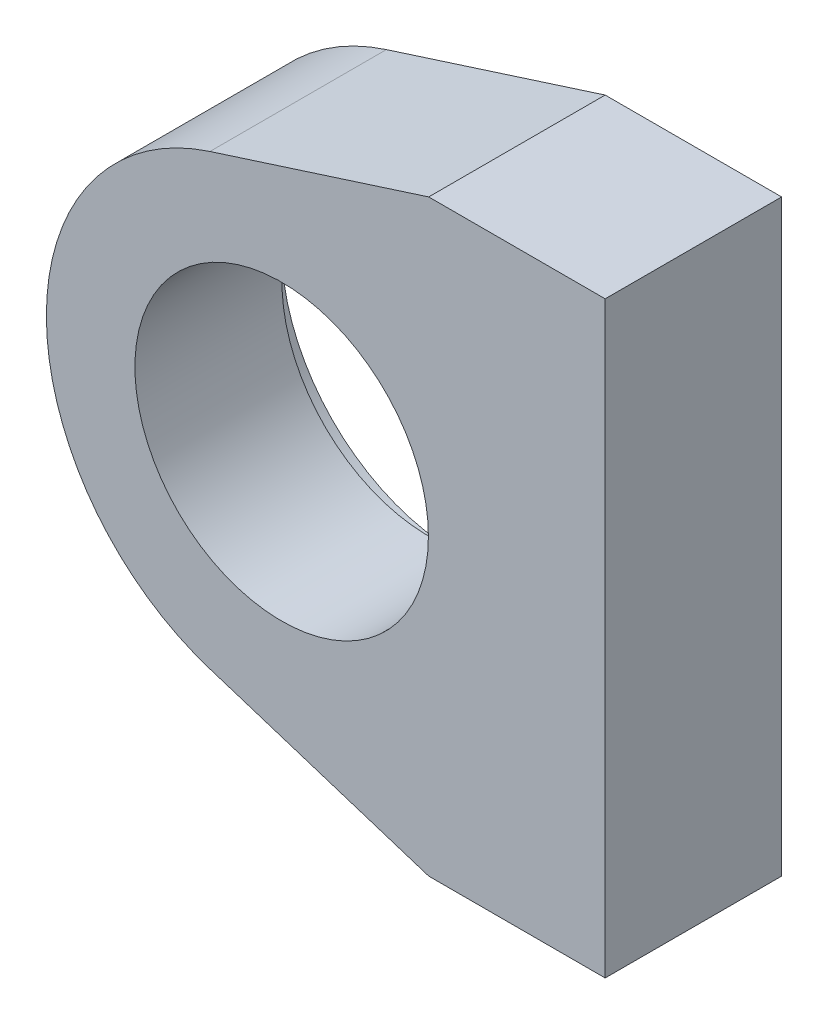
SolidWorks part; units mm, degrees
ref_plane "Front Plane" through (0, 0, 0) normal (0, 0, 1) x (1, 0, 0)
ref_plane "Top Plane" through (0, 0, 0) normal (0, 1, 0) x (1, 0, 0)
ref_plane "Right Plane" through (0, 0, 0) normal (1, 0, 0) x (0, 0, -1)
sketch "Sketch1" plane through (0, 0, 0) normal (0, 0, 1) x (1, 0, 0)
  line L0 (-2.4386, 7.6193) -> (5, 10)
  line L1 (5, -10) -> (11, -10)
  line L2 (-2.4386, -7.6193) -> (5, -10)
  line L3 (5, 10) -> (11, 10)
  line L4 (11, -10) -> (11, 10)
  circle A0 centre (0, 0) radius 4
  arc A1 (-2.4386, 7.6193) -> (-2.4386, -7.6193) centre (0, 0) ccw
  dimension "D5" = 8
  dimension "D2" = 6
  dimension "D3" = 8
  dimension "D1" = 11
  dimension "D4" = 10
  dimension "D6" = 10
extrude "Boss-Extrude1" add sketch "Sketch1" along normal blind 6
sketch "Sketch4" plane through (0, 0, 6) normal (0, 0, 1) x (1, 0, 0)
  circle A0 centre (0, 0) radius 4.99
  dimension "D1" = 9.98
extrude "Cut-Extrude1" cut sketch "Sketch4" against normal up to next
sketch "Sketch6" plane through (0, 0, 0) normal (0, 0, -1) x (-1, 0, 0)
  circle A0 centre (0, 0) radius 6
  dimension "D1" = 12
extrude "Cut-Extrude3" cut sketch "Sketch6" against normal blind 1
